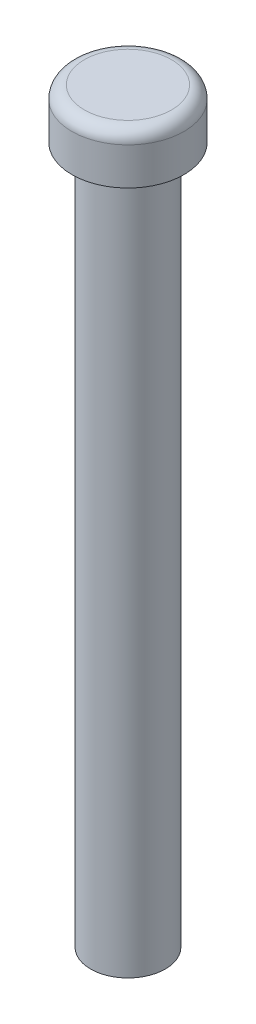
SolidWorks part; units mm, degrees
ref_plane "Front Plane" through (0, 0, 0) normal (0, 0, 1) x (1, 0, 0)
ref_plane "Top Plane" through (0, 0, 0) normal (0, 1, 0) x (1, 0, 0)
ref_plane "Right Plane" through (0, 0, 0) normal (1, 0, 0) x (0, 0, -1)
sketch "Sketch1" plane through (0, 0, 0) normal (0, 1, 0) x (1, 0, 0)
  circle A0 centre (0, 0) radius 1.5
extrude "Boss-Extrude1" add sketch "Sketch1" along normal blind 28
sketch "Sketch2" plane through (0, 28, 0) normal (0, 1, 0) x (1, 0, 0)
  circle A0 centre (0, 0) radius 2.25
  dimension "D1" = 4.5
extrude "Boss-Extrude2" add sketch "Sketch2" along normal blind 2
fillet "Fillet1" radius 0.5 1 edges at (0, 30, 2.25)
